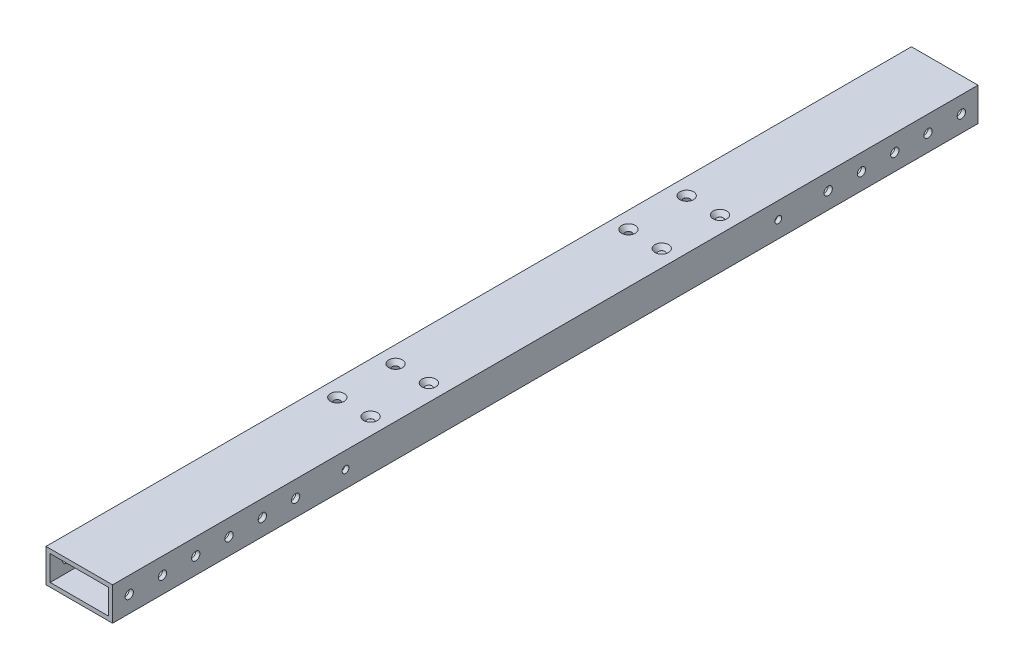
SolidWorks part; units mm, degrees
material "6061 Alloy"
ref_plane "Front Plane" through (0, 0, 0) normal (0, 0, 1) x (1, 0, 0)
ref_plane "Top Plane" through (0, 0, 0) normal (0, 1, 0) x (1, 0, 0)
ref_plane "Right Plane" through (0, 0, 0) normal (1, 0, 0) x (0, 0, -1)
sketch "Sketch1" plane through (0, 0, 0) normal (0, 0, 1) x (1, 0, 0)
  line L0 (-22.225, 9.525) -> (22.225, 9.525)
  line L2 (-25.4, 12.7) -> (25.4, 12.7)
  line L3 (-25.4, 12.7) -> (-25.4, -12.7)
  line L4 (-25.4, -12.7) -> (25.4, -12.7)
  line L5 (25.4, 12.7) -> (25.4, -12.7)
  line L10 (22.225, 9.525) -> (22.225, -9.525)
  line L11 (-22.225, -9.525) -> (22.225, -9.525)
  line L12 (-22.225, 9.525) -> (-22.225, -9.525)
  point P12 (0, 12.7)
  point P14 (25.4, 0)
  dimension "Wall Thickness" = 3.175
  dimension "Outside Width" = 50.8
  dimension "Outside Height" = 25.4
  dimension "Inside Height" = 19.05
  dimension "Inside Width" = 44.45
sketch "Sketch2" plane through (0, 0, 0) normal (1, 0, 0) x (0, 0, -1)
  line L0 (330.2, 0) -> (-330.2, 0)
  point P4 (0, 0)
  point P7 (-330.2, 0)
  point P10 (330.2, 0)
  dimension "Length" = 660.4
sketch "Sketch3" plane through (0, 0, 0) normal (0, 0, 1) x (1, 0, 0)
  line L21 (25.4, 12.7) -> (-25.4, 12.7)
  line L22 (25.4, -12.7) -> (25.4, 12.7)
  line L23 (-25.4, -12.7) -> (25.4, -12.7)
  line L24 (-25.4, 12.7) -> (-25.4, -12.7)
  line L25 (25.4, 12.7) -> (-25.4, 12.7)
  line L26 (25.4, -12.7) -> (25.4, 12.7)
  line L27 (-25.4, -12.7) -> (25.4, -12.7)
  line L28 (-25.4, 12.7) -> (-25.4, -12.7)
  line L29 (22.225, 9.525) -> (-22.225, 9.525)
  line L30 (22.225, -9.525) -> (22.225, 9.525)
  line L31 (-22.225, -9.525) -> (22.225, -9.525)
  line L32 (-22.225, 9.525) -> (-22.225, -9.525)
  line L33 (22.225, 9.525) -> (-22.225, 9.525)
  line L34 (22.225, -9.525) -> (22.225, 9.525)
  line L35 (-22.225, -9.525) -> (22.225, -9.525)
  line L36 (-22.225, 9.525) -> (-22.225, -9.525)
  dimension "D1" = 0
  dimension "D2" = 0
extrude "Boss-Extrude1" add sketch "Sketch3" along normal up to vertex (330.2 mm away) and the other way up to vertex (330.2 mm away) up to point (0, 0, 330.2) other way up to point (0, 0, -330.2)
sketch "Drawing Reference" plane through (0, 0, 0) normal (1, 0, 0) x (0, 0, -1)
  line L0 (-330.2, 0) -> (330.2, 0) construction
  line L1 (0, -12.7) -> (0, 12.7) construction
  line L2 (-330.2, -12.7) -> (330.2, -12.7) construction
  line L5 (-330.2, 12.7) -> (330.2, 12.7) construction
  point P7 (-293.624, 0)
  point P8 (293.624, 0)
  dimension "D1" = 36.576
sketch "Sketch5" plane through (25.4, 0, 0) normal (1, 0, 0) x (0, 0, -1)
  line L2 (-266.7, 0) -> (-241.3, 0)
  line L3 (-241.3, 0) -> (-215.9, 0)
  line L4 (-215.9, 0) -> (-190.5, 0)
  line L5 (-317.5, 0) -> (-330.2, 0)
  line L6 (-330.2, -12.7) -> (-330.2, 12.7) construction
  line L7 (-317.5, 0) -> (-292.1, 0)
  line L8 (-292.1, 0) -> (-266.7, 0)
sketch "Sketch8" plane through (25.4, 0, 0) normal (1, 0, 0) x (0, 0, -1)
  line L0 (330.2, 0) -> (292.1, 0)
  line L1 (330.2, -12.7) -> (330.2, 12.7) construction
  line L2 (292.1, 0) -> (266.7, 0)
  line L3 (266.7, 0) -> (241.3, 0)
  line L4 (241.3, 0) -> (215.9, 0)
  line L5 (330.2, 0) -> (317.5, 0)
hole_wizard "1/4 (0.25) Diameter Hole3" positions "Sketch12" profile "Sketch13" hole size "1/4" standard "ANSI Inch" end condition through all
sketch "Sketch12" plane through (-25.4, 0, 0) normal (-1, 0, 0) x (0, 0, 1)
  point P4 (-317.5, 0)
sketch "Sketch13" plane through (-25.4, 0, -317.5) normal (0, 1, 0) x (0, 0, 1)
  line L0 (0, 0) -> (0, 50.8)
  line L1 (0, 50.8) -> (3.175, 50.8)
  line L2 (3.175, 50.8) -> (3.175, 0)
  line L5 (3.175, 0) -> (0, 0)
  line L11 (0, -6.35) -> (0, 107.95) construction
  dimension "Thru Hole Dia." = 6.35
  dimension "Thru Hole Depth" = 50.8
hole_wizard "1/4 (0.25) Diameter Hole4" positions "Sketch14" profile "Sketch15" hole size "1/4" standard "ANSI Inch" end condition through all
sketch "Sketch14" plane through (-25.4, 0, 0) normal (-1, 0, 0) x (0, 0, 1)
  point P0 (292.1, 0)
  point P3 (317.5, 0)
sketch "Sketch15" plane through (-25.4, 0, 292.1) normal (0, 1, 0) x (0, 0, 1)
  line L0 (0, 0) -> (0, 50.8)
  line L1 (0, 50.8) -> (3.175, 50.8)
  line L2 (3.175, 50.8) -> (3.175, 0)
  line L5 (3.175, 0) -> (0, 0)
  line L11 (0, -6.35) -> (0, 107.95) construction
  dimension "Thru Hole Dia." = 6.35
  dimension "Thru Hole Depth" = 50.8
hole_wizard "1/4 (0.25) Diameter Hole5" positions "Sketch17" profile "Sketch18" hole size "1/4" standard "ANSI Inch" end condition through all
sketch "Sketch17" plane through (25.4, 0, 0) normal (1, 0, 0) x (0, 0, -1)
  point P0 (292.1, 0)
  point P3 (266.7, 0)
sketch "Sketch18" plane through (25.4, 0, -292.1) normal (0, 1, 0) x (0, 0, -1)
  line L0 (0, 0) -> (0, 50.8)
  line L1 (0, 50.8) -> (3.175, 50.8)
  line L2 (3.175, 50.8) -> (3.175, 0)
  line L5 (3.175, 0) -> (0, 0)
  line L11 (0, -6.35) -> (0, 107.95) construction
  dimension "Thru Hole Dia." = 6.35
  dimension "Thru Hole Depth" = 50.8
hole_wizard "1/4 (0.25) Diameter Hole6" positions "Sketch19" profile "Sketch20" hole size "1/4" standard "ANSI Inch" end condition through all
sketch "Sketch19" plane through (25.4, 0, 0) normal (1, 0, 0) x (0, 0, -1)
  point P0 (215.9, 0)
  point P3 (241.3, 0)
sketch "Sketch20" plane through (25.4, 0, -215.9) normal (0, 1, 0) x (0, 0, -1)
  line L0 (0, 0) -> (0, 50.8)
  line L1 (0, 50.8) -> (3.175, 50.8)
  line L2 (3.175, 50.8) -> (3.175, 0)
  line L5 (3.175, 0) -> (0, 0)
  line L11 (0, -6.35) -> (0, 107.95) construction
  dimension "Thru Hole Dia." = 6.35
  dimension "Thru Hole Depth" = 50.8
hole_wizard "1/4 (0.25) Diameter Hole7" positions "Sketch21" profile "Sketch22" hole size "1/4" standard "ANSI Inch" end condition through all
sketch "Sketch21" plane through (25.4, 0, 0) normal (1, 0, 0) x (0, 0, -1)
  point P0 (-190.5, 0)
  point P3 (-215.9, 0)
sketch "Sketch22" plane through (25.4, 0, 190.5) normal (0, 1, 0) x (0, 0, -1)
  line L0 (0, 0) -> (0, 50.8)
  line L1 (0, 50.8) -> (3.175, 50.8)
  line L2 (3.175, 50.8) -> (3.175, 0)
  line L5 (3.175, 0) -> (0, 0)
  line L11 (0, -6.35) -> (0, 107.95) construction
  dimension "Thru Hole Dia." = 6.35
  dimension "Thru Hole Depth" = 50.8
hole_wizard "1/4 (0.25) Diameter Hole8" positions "Sketch23" profile "Sketch24" hole size "1/4" standard "ANSI Inch" end condition through all
sketch "Sketch23" plane through (25.4, 0, 0) normal (1, 0, 0) x (0, 0, -1)
  point P0 (-266.7, 0)
  point P3 (-241.3, 0)
sketch "Sketch24" plane through (25.4, 0, 266.7) normal (0, 1, 0) x (0, 0, -1)
  line L0 (0, 0) -> (0, 50.8)
  line L1 (0, 50.8) -> (3.175, 50.8)
  line L2 (3.175, 50.8) -> (3.175, 0)
  line L5 (3.175, 0) -> (0, 0)
  line L11 (0, -6.35) -> (0, 107.95) construction
  dimension "Thru Hole Dia." = 6.35
  dimension "Thru Hole Depth" = 50.8
sketch "Sketch25" plane through (25.4, 0, 0) normal (1, 0, 0) x (0, 0, -1)
  line L0 (-190.5, 0) -> (-152.4, 0)
  line L1 (215.9, 0) -> (177.8, 0)
hole_wizard "13/64 (0.20313) Diameter Hole1" positions "Sketch26" profile "Sketch27" hole size "13/64" standard "ANSI Inch" end condition through all
sketch "Sketch26" plane through (25.4, 0, 0) normal (1, 0, 0) x (0, 0, -1)
  point P0 (-152.4, 0)
  point P3 (177.8, 0)
sketch "Sketch27" plane through (25.4, 0, 152.4) normal (0, 1, 0) x (0, 0, -1)
  line L0 (0, 0) -> (0, 50.8)
  line L1 (0, 50.8) -> (2.5798, 50.8)
  line L2 (2.5798, 50.8) -> (2.5798, 0)
  line L5 (2.5798, 0) -> (0, 0)
  line L11 (0, -6.35) -> (0, 107.95) construction
  dimension "Thru Hole Dia." = 5.1595
  dimension "Thru Hole Depth" = 50.8
hole_wizard "1/2 (0.5) Diameter Hole1" positions "Sketch33" profile "Sketch34" hole size "1/2" standard "ANSI Inch"
sketch "Sketch33" plane through (-25.4, 0, 0) normal (-1, 0, 0) x (0, 0, 1)
  point P0 (-146.05, 0)
  point P3 (120.65, 0)
sketch "Sketch34" plane through (-25.4, 0, -146.05) normal (0, 1, 0) x (0, 0, 1)
  line L0 (0, 0) -> (0, 10.1655)
  line L1 (0, 10.1655) -> (6.35, 6.35)
  line L2 (6.35, 6.35) -> (6.35, 0)
  line L5 (6.35, 0) -> (0, 0)
  line L10 (0, 10.1655) -> (-6.35, 6.35) construction
  line L11 (0, -6.35) -> (0, 107.95) construction
  dimension "Hole Dia." = 12.7
  dimension "Hole Depth" = 6.35
  dimension "Drill Angle" = 118
sketch "Sketch35" plane through (0, -12.7, 0) normal (0, -1, 0) x (1, 0, 0)
  line L0 (12.7, -101.5498) -> (-12.7, -101.5498) construction
  line L1 (12.7, 120.5998) -> (-12.7, 120.5998) construction
  line L2 (-12.7, 120.5998) -> (-12.7, 76.1498) construction
  line L3 (-12.7, 76.1498) -> (12.7, 76.1498) construction
  line L4 (12.7, 76.1498) -> (12.7, 120.5998) construction
  line L5 (-12.7, -101.5498) -> (-12.7, -145.9998) construction
  line L6 (-12.7, -145.9998) -> (12.7, -145.9998) construction
  line L7 (12.7, -145.9998) -> (12.7, -101.5498) construction
  point P8 (-12.7, -101.5498)
  point P9 (12.7, -145.9998)
hole_wizard "#10 Clearance Hole1" positions "Sketch39" profile "Sketch40" hole size "#10" standard "ANSI Inch" end condition through all
sketch "Sketch39" plane through (0, -12.7, 0) normal (0, -1, 0) x (-1, 0, 0)
  point P0 (12.7, 145.9998)
  point P3 (-12.7, 145.9998)
  point P6 (-12.7, 101.5498)
  point P9 (12.7, 101.5498)
  point P12 (-12.7, -76.1498)
  point P15 (12.7, -76.1498)
  point P18 (12.7, -120.5998)
  point P21 (-12.7, -120.5998)
sketch "Sketch40" plane through (-12.7, -12.7, -145.9998) normal (1, 0, 0) x (0, 0, -1)
  line L0 (0, 0) -> (0, 25.4)
  line L1 (0, 25.4) -> (5.2197, 25.4)
  line L2 (2.4892, 22.2589) -> (2.4892, 0)
  line L5 (2.4892, 0) -> (0, 0)
  line L7 (5.2197, 25.4) -> (2.4892, 22.2589)
  line L8 (-5.2197, 25.4) -> (-2.4892, 22.2589) construction
  line L11 (0, -6.35) -> (0, 107.95) construction
  dimension "Thru Hole Dia." = 4.9784
  dimension "Thru Hole Depth" = 25.4
  dimension "Far C'Sink Dia." = 10.4394
  dimension "Far C'Sink Angle" = 82
equation "\"D1@Drawing Reference\"=\"Outside Width@Sketch1\" * 0.72"
